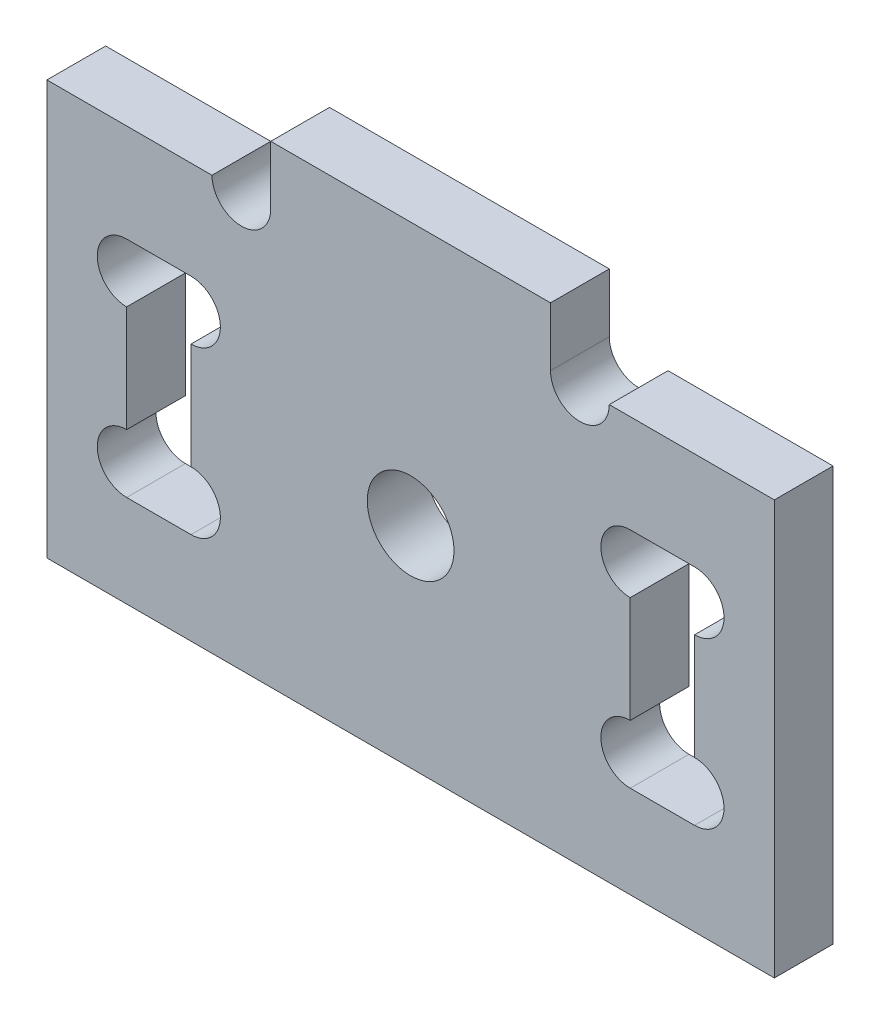
SolidWorks part; units mm, degrees
material "Thornel Mat VMA"
ref_plane "前视基准面" through (0, 0, 0) normal (0, 0, 1) x (1, 0, 0)
ref_plane "上视基准面" through (0, 0, 0) normal (0, 1, 0) x (1, 0, 0)
ref_plane "右视基准面" through (0, 0, 0) normal (1, 0, 0) x (0, 0, -1)
sketch "草图1" plane through (0, 0, 0) normal (0, 0, 1) x (1, 0, 0)
  line L0 (0, 0.1) -> (0, 9.5) construction
  line L1 (13, -7.4) -> (-13, -7.4)
  line L2 (13, -7.4) -> (13, 7.4)
  line L3 (13, 7.4) -> (5, 7.4)
  line L4 (-13, -7.4) -> (-13, 7.4)
  line L5 (13, -7.4) -> (-13, 7.4) construction
  line L6 (13, 7.4) -> (-13, -7.4) construction
  line L7 (-7.85, -4.1) -> (-10.15, -4.1)
  line L8 (-7.85, -4.1) -> (-7.85, 3.9)
  line L9 (-7.85, 3.9) -> (-10.15, 3.9)
  line L10 (-10.15, -4.1) -> (-10.15, 3.9)
  line L11 (-7.85, -4.1) -> (-10.15, 3.9) construction
  line L12 (-7.85, 3.9) -> (-10.15, -4.1) construction
  line L13 (7.85, 3.9) -> (10.15, 3.9)
  line L14 (10.15, -4.1) -> (10.15, 3.9)
  line L15 (7.85, -4.1) -> (10.15, -4.1)
  line L16 (7.85, -4.1) -> (7.85, 3.9)
  line L17 (9, 3.9) -> (9, 0.0975) construction
  line L18 (-5, 7.4) -> (-5, 9.5)
  line L19 (-5, 9.5) -> (5, 9.5)
  line L20 (5, 9.5) -> (5, 7.4)
  line L21 (-5, 7.4) -> (-13, 7.4)
  circle A0 centre (0, 0.1) radius 1.55
  circle A1 centre (-10.15, 2.85) radius 1.05
  circle A2 centre (-7.85, 2.85) radius 1.05
  circle A3 centre (-10.15, -3.05) radius 1.05
  circle A4 centre (-7.85, -3.05) radius 1.05
  circle A5 centre (10.15, -3.05) radius 1.05
  circle A6 centre (10.15, 2.85) radius 1.05
  circle A7 centre (7.85, -3.05) radius 1.05
  circle A8 centre (7.85, 2.85) radius 1.05
  circle A9 centre (6.05, 7.4) radius 1.05
  circle A10 centre (-6.05, 7.4) radius 1.05
  point P0 (0, 0)
  point P8 (-9, -0.1)
  dimension "D1" = 3.1
  dimension "D5" = 2.1
  dimension "D2" = 7.3
  dimension "D3" = 26
  dimension "D4" = 7.5
  dimension "D6" = 8
  dimension "D7" = 7.5
  dimension "D8" = 2.3
  dimension "D9" = 18
  dimension "D10" = 10
  dimension "D11" = 2.1
extrude "凸台-拉伸1" add sketch "草图1" along normal blind 2.1 contours A10 L21 L4 L1 L2 L3 A9 L20 L19 L18 A4 L7 A3 L10 A1 L9 A2 L8 A0 L16 A8 L13 A6 L14 A5 L15 A7
